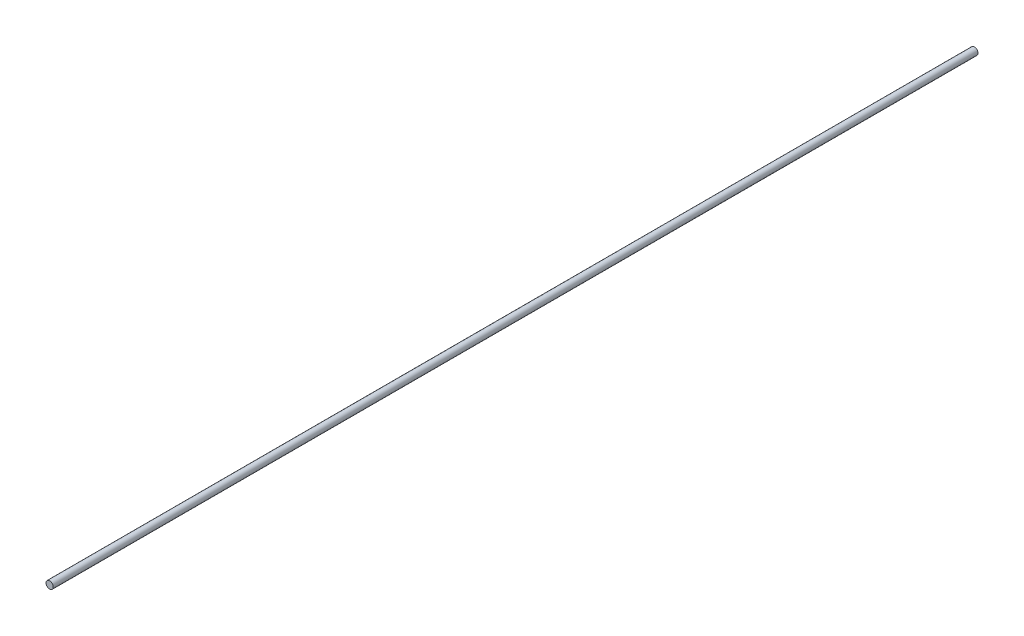
SolidWorks part; units mm, degrees
ref_plane "Front Plane" through (0, 0, 0) normal (0, 0, 1) x (1, 0, 0)
ref_plane "Top Plane" through (0, 0, 0) normal (0, 1, 0) x (1, 0, 0)
ref_plane "Right Plane" through (0, 0, 0) normal (1, 0, 0) x (0, 0, -1)
sketch "Sketch1" plane through (0, 0, 0) normal (0, 0, 1) x (1, 0, 0)
  circle A0 centre (0, 0) radius 1.9844
  dimension "D1" = 3.9688
extrude "Boss-Extrude1" add sketch "Sketch1" along normal blind 508
